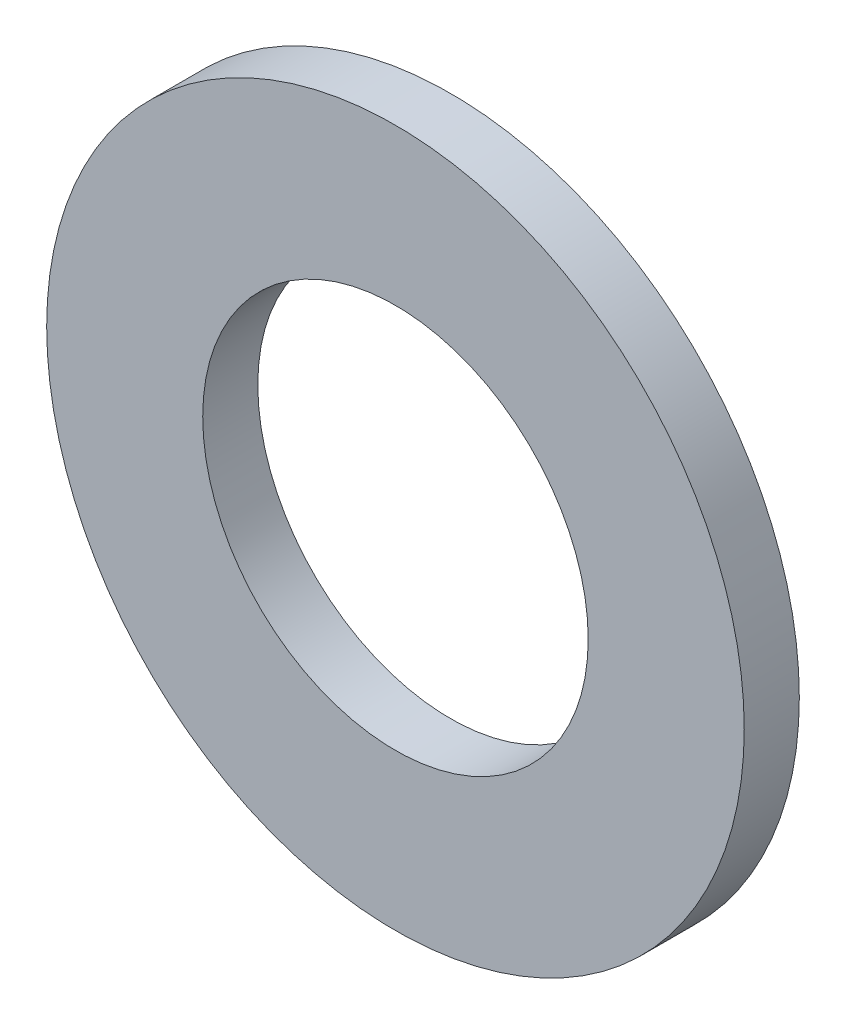
SolidWorks part; units mm, degrees
material "AISI 4340 Steel, normalized"
ref_plane "Front Plane" through (0, 0, 0) normal (0, 0, 1) x (1, 0, 0)
ref_plane "Top Plane" through (0, 0, 0) normal (0, 1, 0) x (1, 0, 0)
ref_plane "Right Plane" through (0, 0, 0) normal (1, 0, 0) x (0, 0, -1)
sketch "Sketch1" plane through (0, 0, 0) normal (0, 0, 1) x (1, 0, 0)
  circle A0 centre (0, 0) radius 1.9
  circle A1 centre (0, 0) radius 1.05
extrude "Washer" add sketch "Sketch1" along normal blind 0.3
